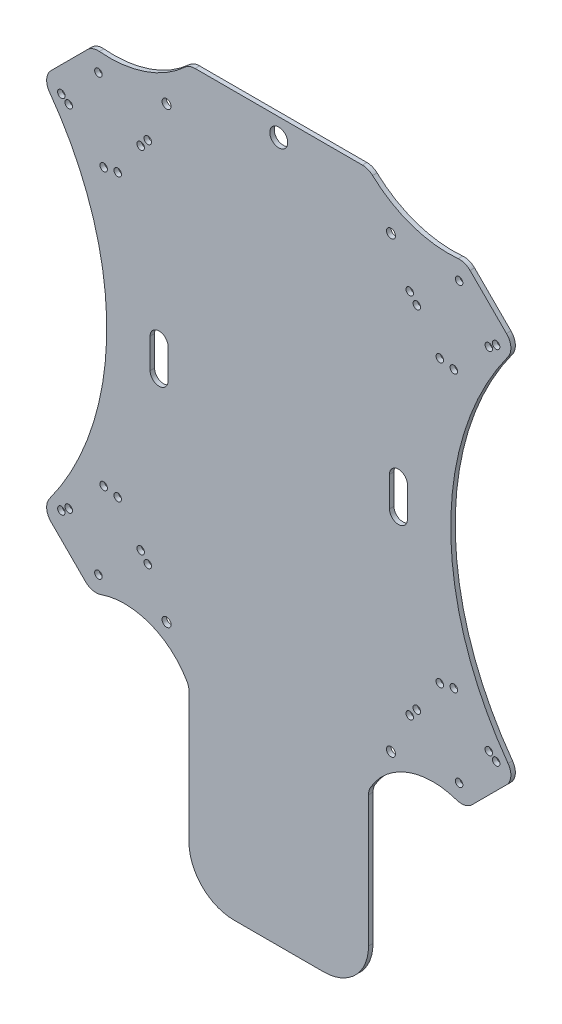
SolidWorks part; units mm, degrees
material "Carbon Fibre 3K"
ref_plane "Front Plane" through (0, 0, 0) normal (0, 0, 1) x (1, 0, 0)
ref_plane "Top Plane" through (0, 0, 0) normal (0, 1, 0) x (1, 0, 0)
ref_plane "Right Plane" through (0, 0, 0) normal (1, 0, 0) x (0, 0, -1)
sketch "Sketch2" plane through (0, 0, 0) normal (0, 0, 1) x (1, 0, 0)
  line L0 (0, 0) -> (0, 50000) construction
  line L1 (0, 0) -> (35355.3391, 35355.3391) construction
  line L2 (0, 0) -> (35355.3391, -35355.3391) construction
  line L3 (-79.196, 62.2254) -> (-62.2254, 79.196)
  line L4 (13.5022, 0) -> (-49986.4978, 0) construction
  line L5 (-79.196, -62.2254) -> (-62.2254, -79.196)
  line L6 (30, 90) -> (-30, 90)
  line L7 (30, -90) -> (30, -135)
  line L8 (79.196, -62.2254) -> (62.2254, -79.196)
  line L9 (-30, -90) -> (-30, -135)
  line L10 (-15, -150) -> (15, -150)
  line L11 (79.196, 62.2254) -> (62.2254, 79.196)
  line L12 (-30, -90) -> (30, -150) construction
  line L13 (-30, -150) -> (30, -90) construction
  line L14 (40, 5) -> (40, -5) construction
  line L15 (43, 5) -> (43, -5)
  line L16 (37, 5) -> (37, -5)
  line L17 (-40, 5) -> (-40, -5) construction
  line L18 (-43, 5) -> (-43, -5)
  line L19 (-37, 5) -> (-37, -5)
  arc A0 (-79.196, 62.2254) -> (-79.196, -62.2254) centre (-157.4775, 0) cw
  arc A1 (-62.2254, 79.196) -> (-30, 90) centre (-56.6326, 115.976) ccw
  arc A2 (-62.2254, -79.196) -> (-30, -90) centre (-51.5147, -100.7107) cw
  arc A3 (15, -150) -> (30, -135) centre (15, -135) ccw
  arc A4 (-15, -150) -> (-30, -135) centre (-15, -135) cw
  arc A5 (62.2254, -79.196) -> (30, -90) centre (51.5147, -100.7107) ccw
  arc A6 (79.196, 62.2254) -> (79.196, -62.2254) centre (157.4775, 0) ccw
  arc A7 (62.2254, 79.196) -> (30, 90) centre (56.6326, 115.976) cw
  circle A8 centre (-37.5, 75) radius 1.5
  circle A9 centre (37.5, 75) radius 1.5
  circle A10 centre (37.5, -75) radius 1.5
  circle A11 centre (-37.5, -75) radius 1.5
  circle A12 centre (0, 84) radius 3
  arc A13 (43, 5) -> (37, 5) centre (40, 5) ccw
  arc A14 (37, -5) -> (43, -5) centre (40, -5) ccw
  arc A15 (-43, 5) -> (-37, 5) centre (-40, 5) cw
  arc A16 (-37, -5) -> (-43, -5) centre (-40, -5) cw
  point P16 (-70.7107, 70.7107)
  point P24 (0, -120)
  point P32 (0, -150)
  point P45 (0, 90)
  point P51 (40, 0)
  point P58 (-40, 0)
  dimension "D9" = 40
  dimension "D4" = 75
  dimension "D8" = 6
  dimension "D1" = 150
  dimension "D2" = 45
  dimension "D3" = 45
  dimension "D5" = 30
  dimension "D6" = 60
  dimension "D7" = 37.5
extrude "Boss-Extrude1" add sketch "Sketch2" along normal blind 1.5
sketch "Sketch3" plane through (0, 0, 1.5) normal (0, 0, 1) x (1, 0, 0)
  line L0 (-70.7107, 70.7107) -> (35284.6284, -35284.6284) construction
  line L1 (-79.196, 62.2254) -> (-62.2254, 79.196) construction
  line L2 (0, 90) -> (0, 50090) construction
  line L3 (30, 90) -> (-30, 90) construction
  line L4 (70.7107, 70.7107) -> (35426.0497, 35426.0497) construction
  line L5 (79.196, 62.2254) -> (62.2254, 79.196) construction
  line L6 (0, 0) -> (50000, 0) construction
  circle A0 centre (-72.6552, 60.2809) radius 1.25
  circle A1 centre (-58.5131, 46.1387) radius 1.25
  circle A2 centre (-60.2809, 72.6552) radius 1.25
  circle A3 centre (-46.1387, 58.5131) radius 1.25
  circle A4 centre (58.5131, 46.1387) radius 1.25
  circle A5 centre (72.6552, 60.2809) radius 1.25
  circle A6 centre (60.2809, 72.6552) radius 1.25
  circle A7 centre (46.1387, 58.5131) radius 1.25
  circle A8 centre (-58.5131, -46.1387) radius 1.25
  circle A9 centre (-46.1387, -58.5131) radius 1.25
  circle A10 centre (-60.2809, -72.6552) radius 1.25
  circle A11 centre (-72.6552, -60.2809) radius 1.25
  circle A12 centre (58.5131, -46.1387) radius 1.25
  circle A13 centre (72.6552, -60.2809) radius 1.25
  circle A14 centre (60.2809, -72.6552) radius 1.25
  circle A15 centre (46.1387, -58.5131) radius 1.25
  point P6 (-70.7107, 70.7107)
  point P17 (0, 90)
  point P30 (70.7107, 70.7107)
  dimension "D1" = 8.75
  dimension "D3" = 8.75
  dimension "D2" = 6
  dimension "D4" = 20
  dimension "D5" = 6
extrude "45 Degrees" cut sketch "Sketch3" against normal through all
sketch "Sketch4" plane through (0, 0, 1.5) normal (0, 0, 1) x (1, 0, 0)
  line L0 (-60.2809, 71.5946) -> (-60.2809, -49928.4054) construction
  line L1 (-62.7557, 72.6552) -> (49937.2443, 72.6552) construction
  line L2 (-61.5934, 70.7807) -> (-28740.4152, -40886.8215) construction
  line L3 (-66.3406, 66.4749) -> (40891.2616, -28612.347) construction
  line L4 (0, 0) -> (0, 50000) construction
  line L5 (0, 0) -> (50000, 0) construction
  circle A1 centre (-70.1971, 58.4934) radius 1.25
  circle A2 centre (-60.2809, 72.6552) radius 1.25
  circle A3 centre (60.2809, 72.6552) radius 1.25
  circle A4 centre (-43.7773, 61.3577) radius 1.25
  circle A5 centre (-53.814, 47.0219) radius 1.25
  circle A6 centre (43.7773, 61.3577) radius 1.25
  circle A7 centre (53.814, 47.0219) radius 1.25
  circle A8 centre (70.1971, 58.4934) radius 1.25
  circle A9 centre (60.2809, -72.6552) radius 1.25
  circle A10 centre (70.1971, -58.4934) radius 1.25
  circle A11 centre (43.7773, -61.3577) radius 1.25
  circle A12 centre (53.814, -47.0219) radius 1.25
  circle A13 centre (-60.2809, -72.6552) radius 1.25
  circle A14 centre (-53.814, -47.0219) radius 1.25
  circle A15 centre (-43.7773, -61.3577) radius 1.25
  circle A16 centre (-70.1971, -58.4934) radius 1.25
  dimension "D3" = 20
  dimension "D2" = 8.75
  dimension "D4" = 8.75
  dimension "D5" = 8.75
  dimension "D6" = 20
extrude "35 Degress" cut sketch "Sketch4" against normal through all
fillet "Fillet1" radius 5 1 edges at (-30, 90, 0.75)
fillet "Fillet2" radius 5 1 edges at (-79.196, 62.2254, 0.75)
fillet "Fillet3" radius 5 1 edges at (-62.2254, 79.196, 0.75)
fillet "Fillet4" radius 5 1 edges at (62.2254, 79.196, 0.75)
fillet "Fillet5" radius 5 1 edges at (30, 90, 0.75)
fillet "Fillet6" radius 5 1 edges at (79.196, 62.2254, 0.75)
fillet "Fillet7" radius 5 1 edges at (79.196, -62.2254, 0.75)
fillet "Fillet8" radius 5 1 edges at (62.2254, -79.196, 0.75)
fillet "Fillet10" radius 5 1 edges at (30, -90, 0.75)
fillet "Fillet11" radius 5 1 edges at (-30, -90, 0.75)
fillet "Fillet12" radius 5 1 edges at (-79.196, -62.2254, 0.75)
fillet "Fillet13" radius 5 1 edges at (-62.2254, -79.196, 0.75)
